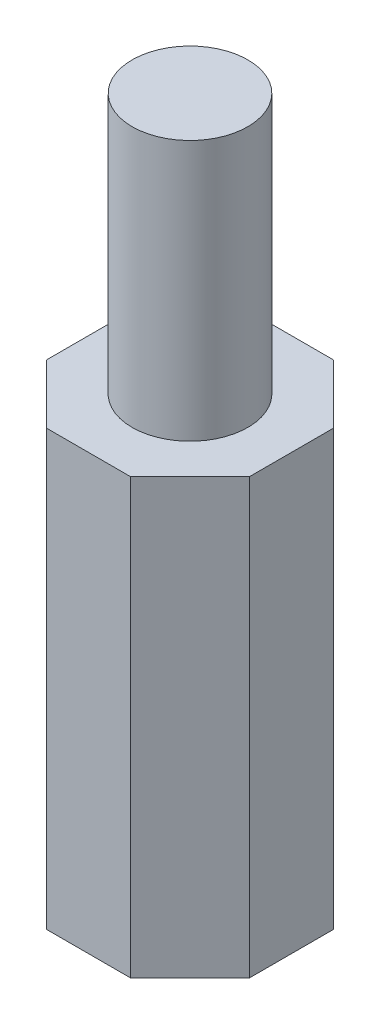
SolidWorks part; units mm, degrees
ref_plane "Plan de face" through (0, 0, 0) normal (0, 0, 1) x (1, 0, 0)
ref_plane "Plan de dessus" through (0, 0, 0) normal (0, 1, 0) x (1, 0, 0)
ref_plane "Plan de droite" through (0, 0, 0) normal (1, 0, 0) x (0, 0, -1)
sketch "Esquisse1" plane through (0, 0, 0) normal (0, 1, 0) x (1, 0, 0)
  line L0 (-1.4497, 3.5) -> (1.4497, 3.5)
  line L1 (1.4497, 3.5) -> (3.5, 1.4497)
  line L2 (3.5, 1.4497) -> (3.5, -1.4497)
  line L3 (3.5, -1.4497) -> (1.4497, -3.5)
  line L4 (1.4497, -3.5) -> (-1.4497, -3.5)
  line L5 (-1.4497, -3.5) -> (-3.5, -1.4497)
  line L6 (-3.5, -1.4497) -> (-3.5, 1.4497)
  line L7 (-3.5, 1.4497) -> (-1.4497, 3.5)
  line L8 (0, 3.5) -> (0, -3.5) construction
  dimension "D1" = 7
extrude "Extrusion1" add sketch "Esquisse1" along normal mid plane 15
sketch "Esquisse2" plane through (0, 7.5, 0) normal (0, 1, 0) x (1, 0, 0)
  circle A0 centre (0, 0) radius 2
  dimension "D1" = 4
extrude "Extrusion2" add sketch "Esquisse2" along normal blind 9
sketch "Esquisse3" plane through (0, -7.5, 0) normal (0, -1, 0) x (1, 0, 0)
  circle A0 centre (0, 0) radius 2
  dimension "D1" = 4
extrude "Enlèv. mat.-Extru.1" cut sketch "Esquisse3" against normal blind 9
